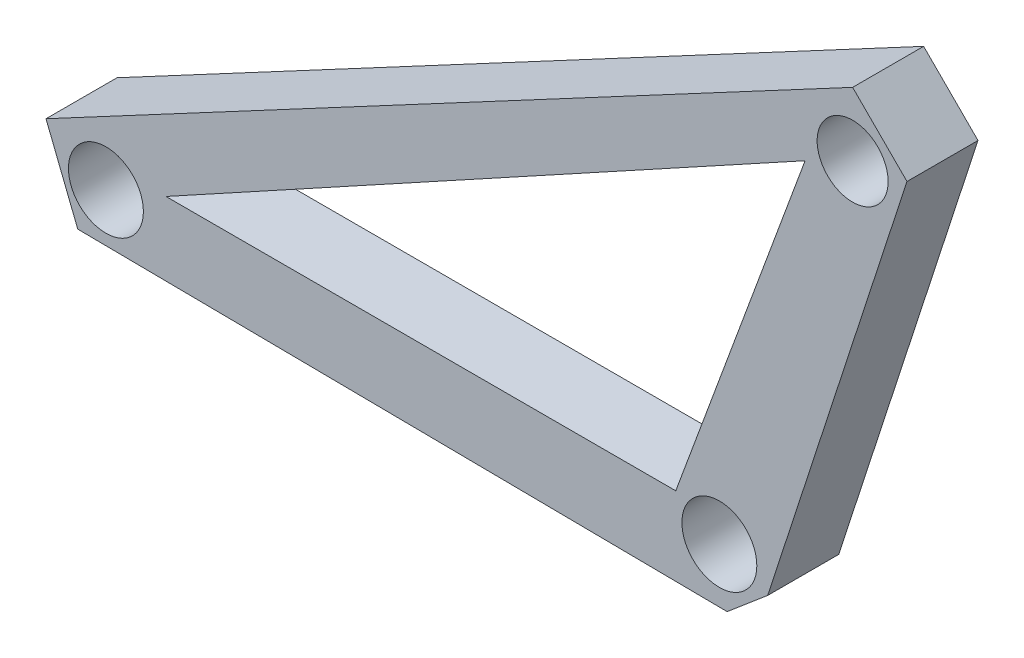
SolidWorks part; units mm, degrees
ref_plane "前视基准面" through (0, 0, 0) normal (0, 0, 1) x (1, 0, 0)
ref_plane "上视基准面" through (0, 0, 0) normal (0, 1, 0) x (1, 0, 0)
ref_plane "右视基准面" through (0, 0, 0) normal (1, 0, 0) x (0, 0, -1)
sketch "草图1" plane through (0, 0, 0) normal (0, 0, 1) x (1, 0, 0)
  line L3 (39.0917, 5.3128) -> (130.5434, 4.3886)
  line L6 (130.5434, 4.3886) -> (136.2514, 9.2184)
  line L7 (34.6192, 16.5437) -> (148.2162, 77.1706)
  line L11 (51.5152, 15.5111) -> (141.5203, 64.8712)
  line L14 (51.5152, 15.5111) -> (123.307, 15.5111)
  line L15 (141.5203, 64.8712) -> (123.307, 15.5111)
  line L17 (148.2162, 77.1706) -> (155.8711, 69.5157)
  line L18 (155.8711, 69.5157) -> (136.2514, 9.2184)
  line L19 (34.6192, 16.5437) -> (39.0917, 5.3128)
  circle A0 centre (43.0576, 12.0738) radius 5.2767
  circle A1 centre (129.4457, 12.0738) radius 5.2767
  circle A3 centre (148.2162, 68.1643) radius 5
  point P8 (34.6192, 16.5437)
  point P10 (51.5152, 15.5111)
  dimension "D2" = 128.763
extrude "凸台-拉伸1" add sketch "草图1" along normal blind 10
